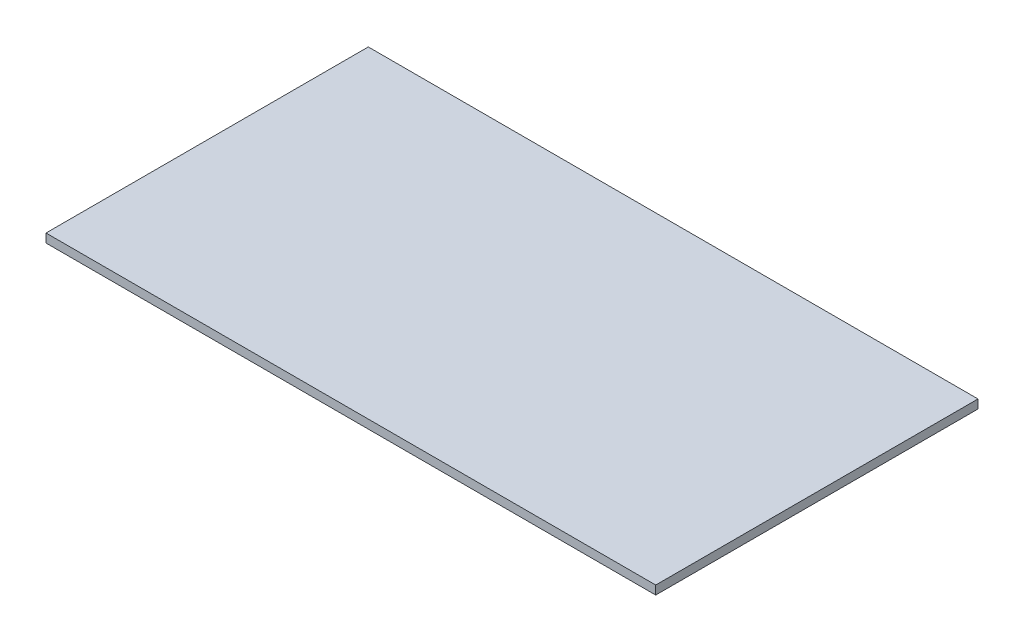
SolidWorks part; units mm, degrees
ref_plane "Front Plane" through (0, 0, 0) normal (0, 0, 1) x (1, 0, 0)
ref_plane "Top Plane" through (0, 0, 0) normal (0, 1, 0) x (1, 0, 0)
ref_plane "Right Plane" through (0, 0, 0) normal (1, 0, 0) x (0, 0, -1)
sketch "Sketch1" plane through (0, 0, 0) normal (0, 1, 0) x (1, 0, 0)
  line L1 (175, -92.5) -> (-175, -92.5)
  line L2 (175, -92.5) -> (175, 92.5)
  line L3 (175, 92.5) -> (-175, 92.5)
  line L4 (-175, -92.5) -> (-175, 92.5)
  line L5 (175, -92.5) -> (-175, 92.5) construction
  line L6 (175, 92.5) -> (-175, -92.5) construction
  point P0 (0, 0)
  dimension "D1" = 350
  dimension "D2" = 185
extrude "Boss-Extrude1" add sketch "Sketch1" along normal blind 5
sketch "Sketch2" plane through (0, 5, 0) normal (0, 1, 0) x (1, 0, 0)
  line L0 (-175, 92.5) -> (-175, -92.5) construction
  line L1 (175, -92.5) -> (175, 92.5) construction
  spline S0 degree 3 poles (-175, -40.4304) (-154.2614, -77.3177) (-53.8751, -55.1514) (-88.3907, 77.3547) (23.6876, 66.4961) (29.9589, -0.8325) (115.9494, -82.891) (136.9497, 94.3697) (175, 6.7706) knots 0 0 0 0 0.192198 0.387582 0.490055 0.65338 0.74052 1 1 1 1
